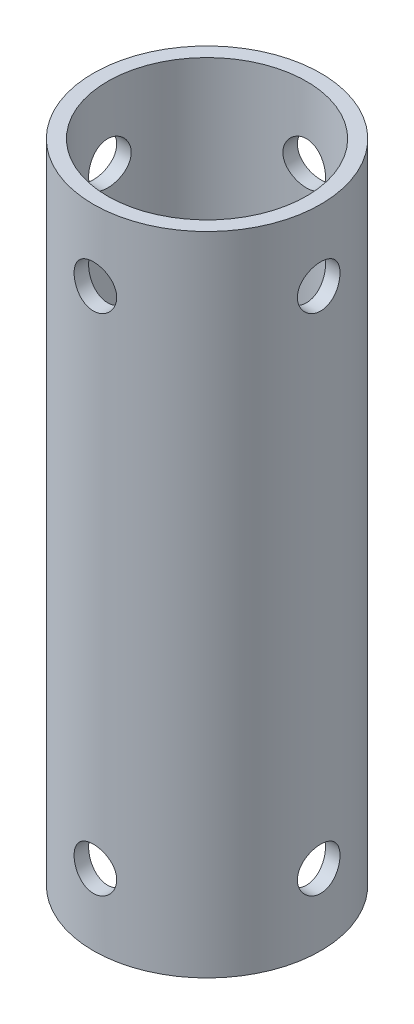
SolidWorks part; units mm, degrees
ref_plane "Front Plane" through (0, 0, 0) normal (0, 0, 1) x (1, 0, 0)
ref_plane "Top Plane" through (0, 0, 0) normal (0, 1, 0) x (1, 0, 0)
ref_plane "Right Plane" through (0, 0, 0) normal (1, 0, 0) x (0, 0, -1)
sketch "Sketch1" plane through (0, 0, 0) normal (0, 1, 0) x (1, 0, 0)
  circle A0 centre (0, 0) radius 14
  circle A1 centre (0, 0) radius 16
  dimension "D1" = 28
  dimension "D2" = 32
extrude "Boss-Extrude1" add sketch "Sketch1" along normal blind 91
ref_plane "Plane1" through (0, 0, -16) normal (0, 0, -1) x (-1, 0, 0)
sketch "Sketch2" plane through (0, 0, -16) normal (0, 0, -1) x (-1, 0, 0)
  line L0 (0, 0) -> (0, 91) construction
  line L1 (16, 91) -> (-16, 91) construction
  line L2 (-16, 0) -> (16, 0) construction
  line L4 (14, 91) -> (-14, 91) construction
  circle A0 centre (0, 10) radius 3
  circle A1 centre (0, 81) radius 3
  dimension "D2" = 6
  dimension "D3" = 6
  dimension "D1" = 10
  dimension "D4" = 10
extrude "Cut-Extrude1" cut sketch "Sketch2" against normal blind 10
ref_axis "Axis1" through (0, 91, 0) along (0, -1, 0)
pattern_circular "CirPattern1" count 4 over 360 about axis through (0, 91, 0) along (0, -1, 0) of "Cut-Extrude1"
